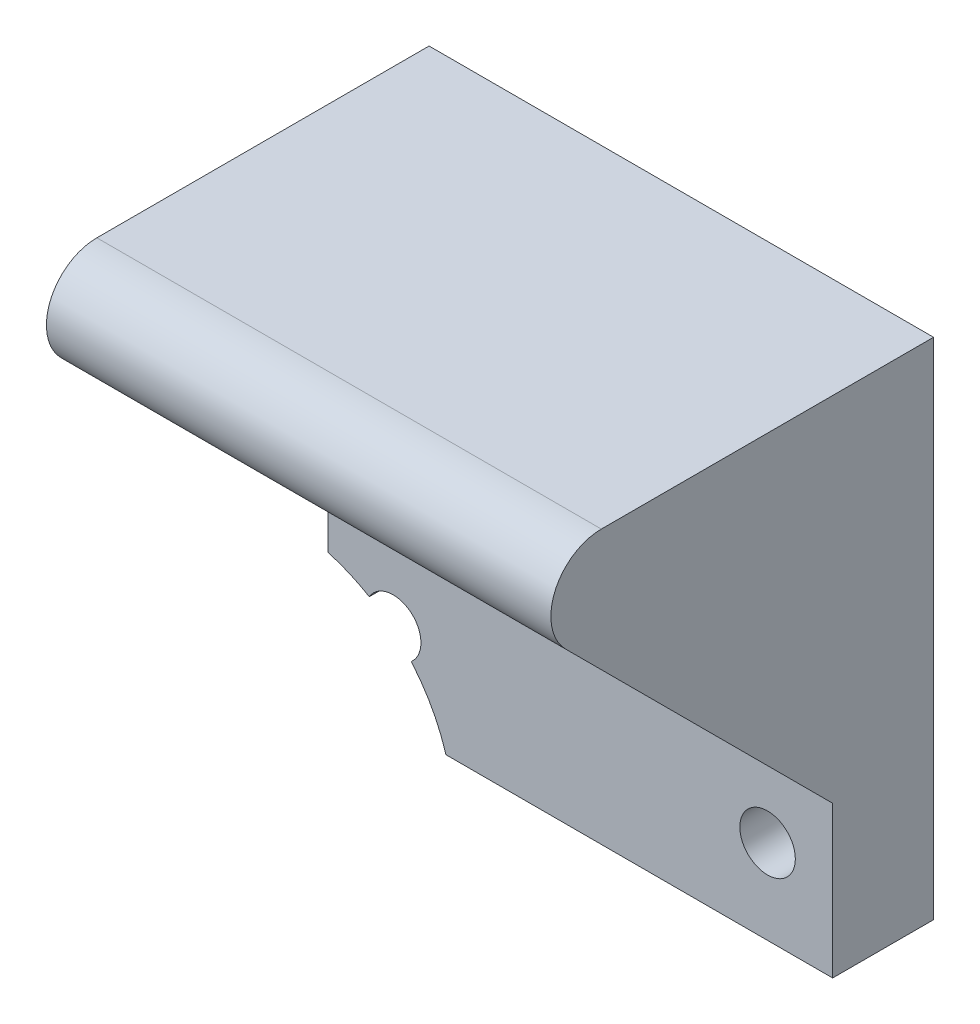
SolidWorks part; units mm, degrees
ref_plane "Front Plane" through (0, 0, 0) normal (0, 0, 1) x (1, 0, 0)
ref_plane "Top Plane" through (0, 0, 0) normal (0, 1, 0) x (1, 0, 0)
ref_plane "Right Plane" through (0, 0, 0) normal (1, 0, 0) x (0, 0, -1)
sketch "Sketch2" plane through (0, 0, 0) normal (1, 0, 0) x (0, 0, -1)
  line L0 (0, 0) -> (0, 50)
  line L1 (0, 50) -> (-45, 50)
  line L2 (-45, 50) -> (-10, 15)
  line L3 (-10, 15) -> (-10, 0)
  line L4 (-10, 0) -> (0, 0)
  dimension "D1" = 10
  dimension "D2" = 45
  dimension "D3" = 15
  dimension "D4" = 50
extrude "Boss-Extrude1" add sketch "Sketch2" along normal blind 50
sketch "Sketch3" plane through (0, 0, 10) normal (0, 0, 1) x (1, 0, 0)
  circle A0 centre (-4.6266, -4.8434) radius 17
  dimension "D1" = 34
extrude "Cut-Extrude1" cut sketch "Sketch3" against normal blind 10
sketch "Sketch4" plane through (0, 0, 10) normal (0, 0, 1) x (1, 0, 0)
  circle A0 centre (6.4413, 8.3666) radius 2.75
  circle A1 centre (43.5502, 8.3666) radius 2.75
  dimension "D1" = 5.5
extrude "Cut-Extrude2" cut sketch "Sketch4" against normal blind 30
fillet "Fillet1" radius 5 1 edges at (25, 50, 45)
